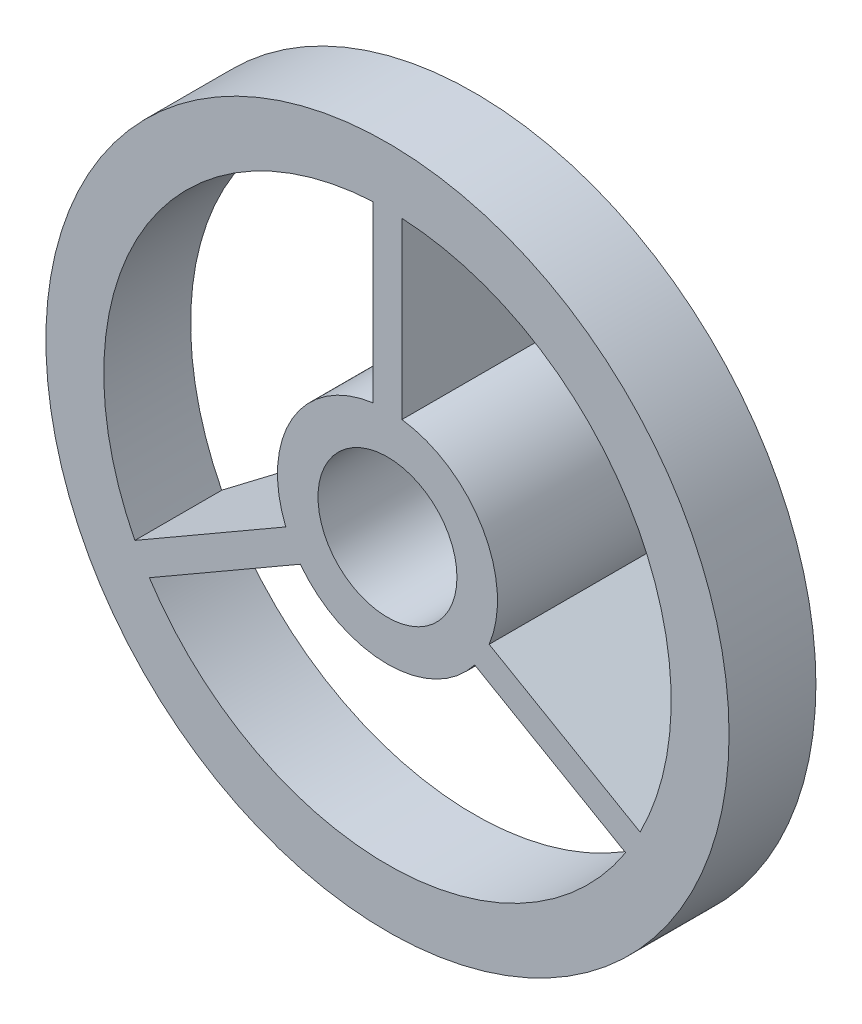
SolidWorks part; units mm, degrees
ref_plane "Front Plane" through (0, 0, 0) normal (0, 0, 1) x (1, 0, 0)
ref_plane "Top Plane" through (0, 0, 0) normal (0, 1, 0) x (1, 0, 0)
ref_plane "Right Plane" through (0, 0, 0) normal (1, 0, 0) x (0, 0, -1)
sketch "Sketch1" plane through (0, 0, 0) normal (0, 0, 1) x (1, 0, 0)
  circle A0 centre (0, 0) radius 1.2
  circle A1 centre (0, 0) radius 1.9
  dimension "D1" = 2.4
  dimension "D2" = 0.7
extrude "Boss-Extrude1" add sketch "Sketch1" along normal blind 3.5
sketch "Sketch2" plane through (0, 0, 3.5) normal (0, 0, 1) x (1, 0, 0)
  circle A1 centre (0, 0) radius 5.9
  circle A2 centre (0, 0) radius 4.9
  circle A3 centre (0, 0) radius 4.9
  dimension "D1" = 3
  dimension "D2" = 1
extrude "Boss-Extrude2" add sketch "Sketch2" against normal blind 1.5 separate body
sketch "Sketch5" plane through (0, 0, 0) normal (1, 0, 0) x (0, 0, -1)
  line L0 (-3.5, 1.9) -> (0, 1.9) construction
  line L1 (-3.5, 1.9) -> (-3.5, -1.9) construction
  line L2 (-3.5, 4.9) -> (-3.5, -4.9) construction
  line L3 (0, -1.9) -> (0, 1.9) construction
  line L4 (0, 1.9) -> (-2, 4.9)
  line L5 (-2, -4.9) -> (-2, 4.9) construction
  line L6 (-2, 4.9) -> (-3.5, 4.9)
  line L7 (-3.5, 4.9) -> (-3.5, 1.9)
  line L8 (-3.5, 1.7) -> (0, 1.7)
  line L9 (-3.5, 1.9) -> (-3.5, 1.7)
  line L10 (0, 1.7) -> (0, 1.9)
  dimension "D1" = 0.2
extrude "Boss-Extrude3" add sketch "Sketch5" along normal mid plane 0.5
pattern_circular "CirPattern1" count 3 over 360 about axis through (0, 0, 0) along (0, 0, 1) of "Boss-Extrude3"
